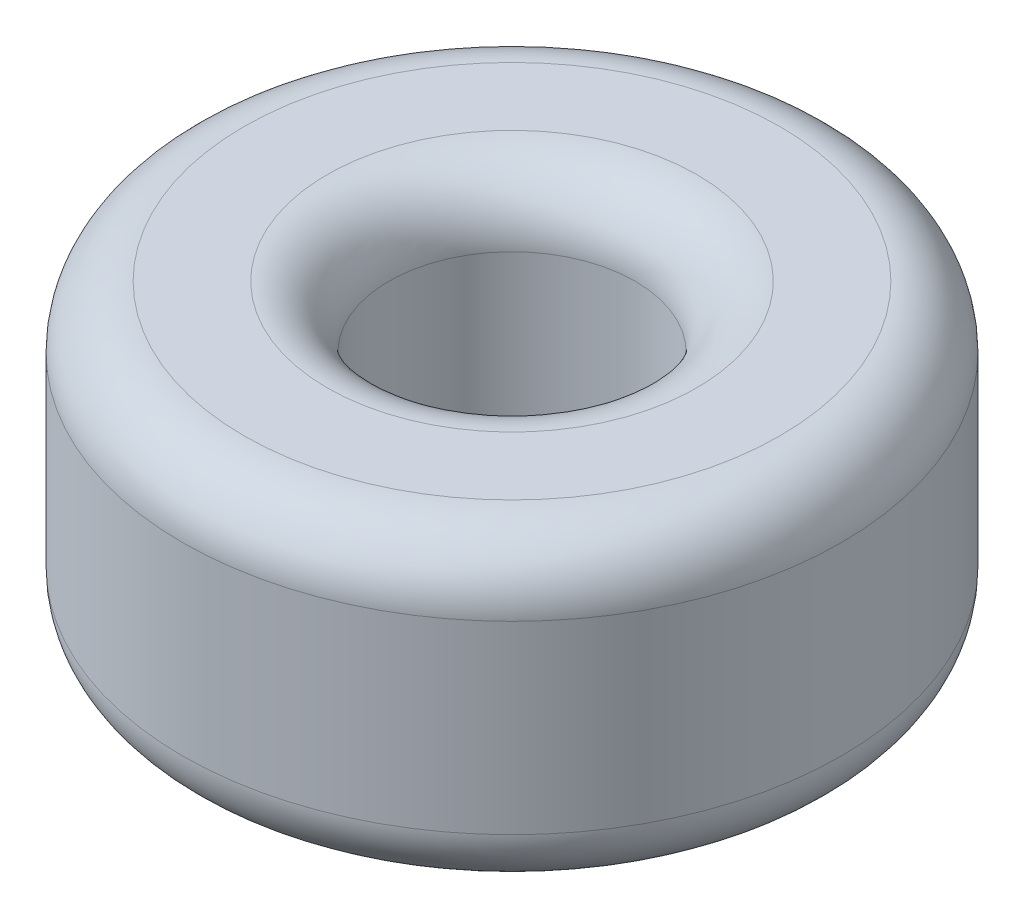
SolidWorks part; units mm, degrees
ref_plane "Front Plane" through (0, 0, 0) normal (0, 0, 1) x (1, 0, 0)
ref_plane "Top Plane" through (0, 0, 0) normal (0, 1, 0) x (1, 0, 0)
ref_plane "Right Plane" through (0, 0, 0) normal (1, 0, 0) x (0, 0, -1)
sketch "Sketch1" plane through (0, 0, 0) normal (0, 1, 0) x (1, 0, 0)
  circle A0 centre (0, 0) radius 53.5
  circle A1 centre (0, 0) radius 20
  dimension "D1" = 107
  dimension "D2" = 40
extrude "Boss-Extrude1" add sketch "Sketch1" along normal blind 50
fillet "Fillet1" radius 10 4 edges at (0, 0, 53.5) (0, 0, 20) (0, 50, 53.5) (0, 50, 20)
